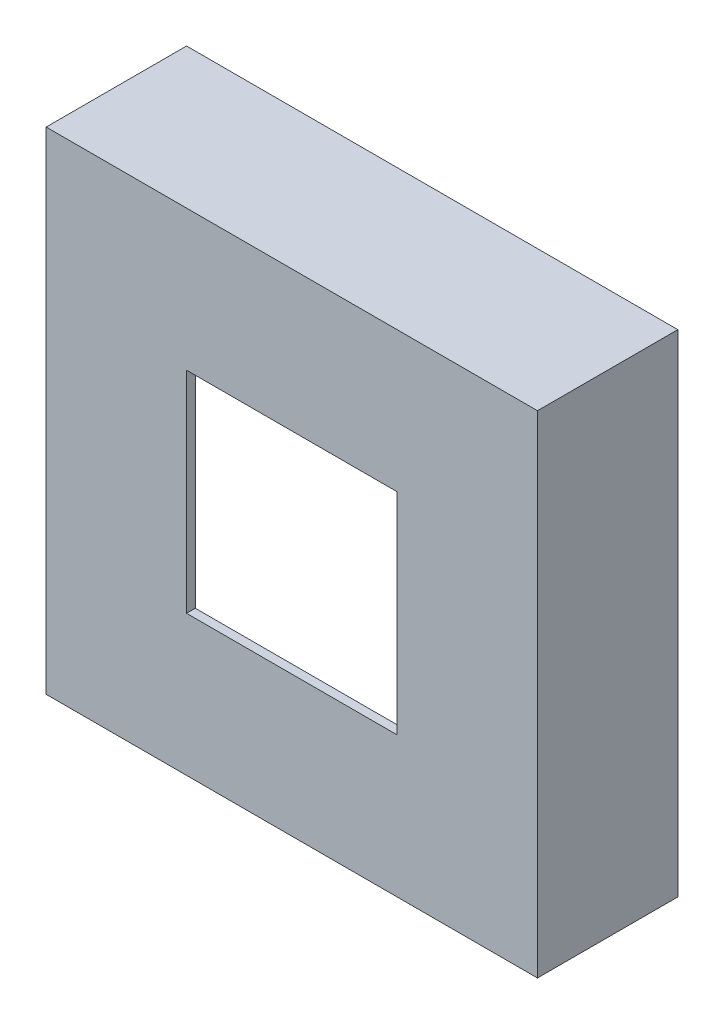
SolidWorks part; units mm, degrees
ref_plane "Front Plane" through (0, 0, 0) normal (0, 0, 1) x (1, 0, 0)
ref_plane "Top Plane" through (0, 0, 0) normal (0, 1, 0) x (1, 0, 0)
ref_plane "Right Plane" through (0, 0, 0) normal (1, 0, 0) x (0, 0, -1)
sketch "Sketch1" plane through (0, 0, 0) normal (0, 0, 1) x (1, 0, 0)
  line L0 (-1, -1) -> (-1, 55)
  line L1 (0, 0) -> (54, 0)
  line L2 (0, 0) -> (0, 54)
  line L3 (0, 54) -> (54, 54)
  line L4 (54, 0) -> (54, 54)
  line L5 (-1, 55) -> (55, 55)
  line L6 (55, -1) -> (55, 55)
  line L7 (-1, -1) -> (55, -1)
  dimension "D1" = 54
  dimension "D2" = 54
  dimension "D3" = 1
extrude "Boss-Extrude1" add sketch "Sketch1" along normal blind 15
sketch "Sketch2" plane through (0, 0, 15) normal (0, 0, 1) x (1, 0, 0)
  line L0 (-1, 55) -> (55, -1) construction
  line L1 (-1, 55) -> (55, 55)
  line L2 (-1, 55) -> (-1, -1)
  line L3 (-1, -1) -> (55, -1)
  line L4 (55, 55) -> (55, -1)
  line L5 (0, 54) -> (0, 0) construction
  line L6 (39, 15) -> (15, 15)
  line L7 (39, 15) -> (39, 39)
  line L8 (39, 39) -> (15, 39)
  line L9 (15, 15) -> (15, 39)
  line L10 (39, 15) -> (15, 39) construction
  line L11 (39, 39) -> (15, 15) construction
  point P6 (27, 27)
  dimension "D1" = 15
extrude "Boss-Extrude2" add sketch "Sketch2" along normal blind 1
